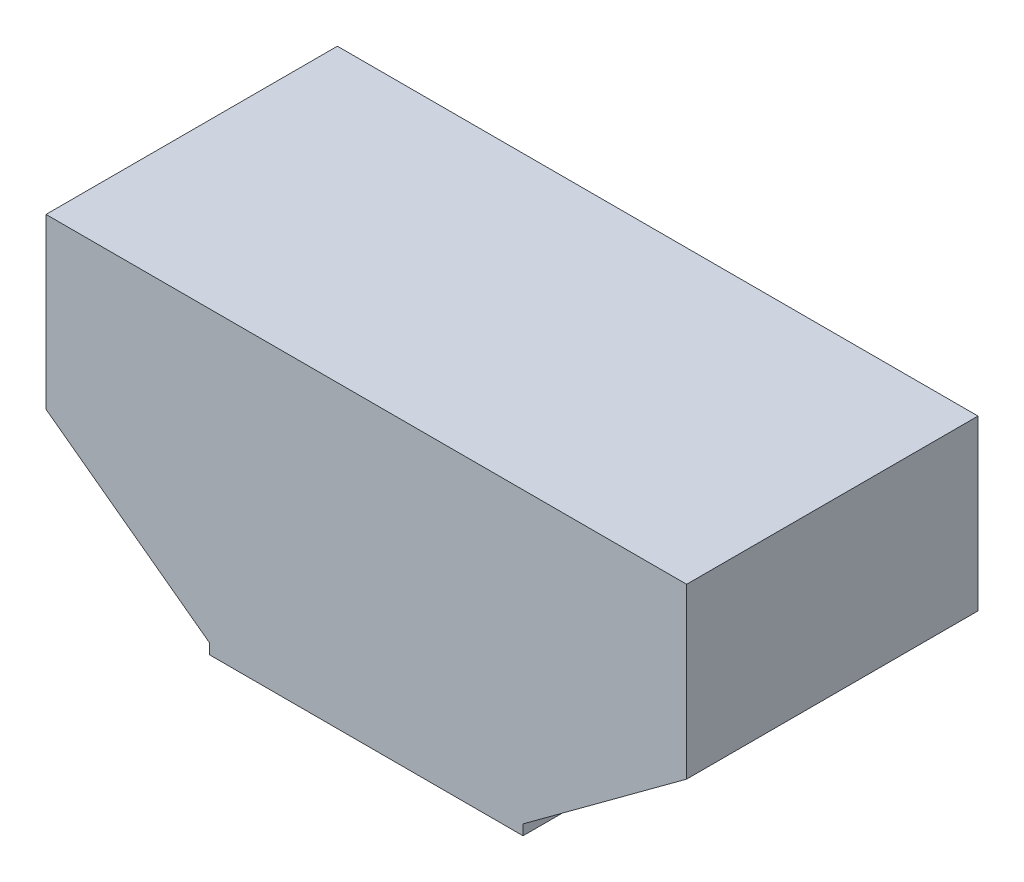
SolidWorks part; units mm, degrees
ref_plane "Front Plane" through (0, 0, 0) normal (0, 0, 1) x (1, 0, 0)
ref_plane "Top Plane" through (0, 0, 0) normal (0, 1, 0) x (1, 0, 0)
ref_plane "Right Plane" through (0, 0, 0) normal (1, 0, 0) x (0, 0, -1)
sketch "Sketch1" plane through (0, 0, 0) normal (0, 0, 1) x (1, 0, 0)
  line L0 (-2063.2072, -609.6) -> (2063.2072, -609.6) construction
  line L1 (-2087.4164, -520.7) -> (2087.4164, -520.7) construction
  line L2 (0, 0) -> (0, -609.6) construction
  line L3 (-577.85, -2072.3236) -> (577.85, -2072.3236)
  line L6 (577.85, -2072.3236) -> (577.85, -2034.2236)
  line L7 (577.85, -2034.2236) -> (-577.85, -2034.2236) construction
  line L8 (-577.85, -2034.2236) -> (-577.85, -2072.3236)
  line L9 (-577.85, -2034.2236) -> (-1181.1, -1589.7236)
  line L10 (-1181.1, -1589.7236) -> (-1181.1, -967.4236)
  line L11 (-1181.1, -967.4236) -> (1181.1, -967.4236)
  line L12 (1181.1, -967.4236) -> (1181.1, -1589.7236)
  line L13 (1181.1, -1589.7236) -> (577.85, -2034.2236)
  circle A0 centre (0, 0) radius 2240.28 construction
  circle A1 centre (0, 0) radius 2151.38 construction
  circle A4 centre (0, -609.6) radius 274.5589 construction
  point P6 (0, -2151.38)
  point P19 (0, -520.7)
  point P20 (0, -609.6)
  point P21 (0, -2034.2236)
  dimension "D1" = 4480.56
  dimension "D2" = 88.9
  dimension "D5" = 1155.7
  dimension "D7" = 622.3
  dimension "D3" = 1541.78
  dimension "D4" = 88.9
  dimension "D6" = 1066.8
  dimension "D8" = 38.1
  dimension "D9" = 2362.2
extrude "Boss-Extrude1" add sketch "Sketch1" along normal blind 1074.42
